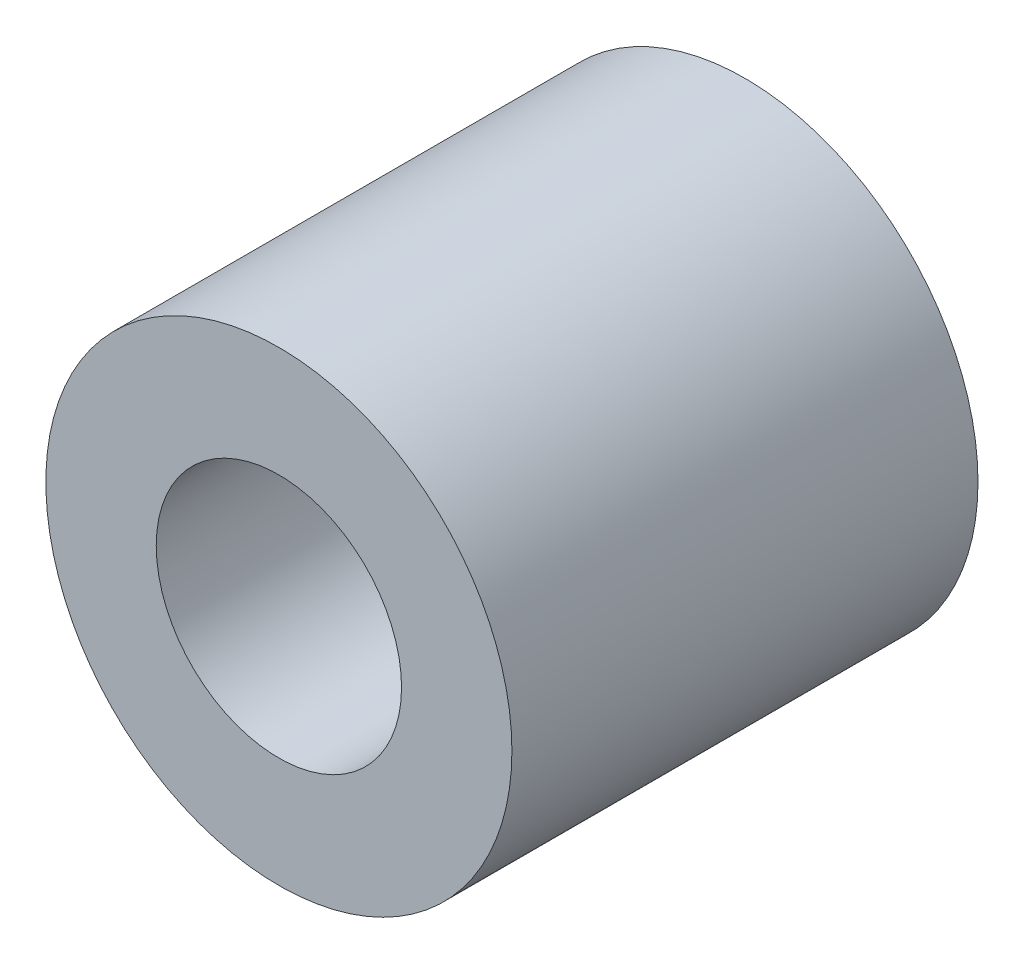
SolidWorks part; units mm, degrees
material "Nylon"
ref_plane "Front Plane" through (0, 0, 0) normal (0, 0, 1) x (1, 0, 0)
ref_plane "Top Plane" through (0, 0, 0) normal (0, 1, 0) x (1, 0, 0)
ref_plane "Right Plane" through (0, 0, 0) normal (1, 0, 0) x (0, 0, -1)
sketch "Sketch1" plane through (0, 0, 0) normal (0, 0, 1) x (1, 0, 0)
  circle A0 centre (0, 0) radius 4.75
  dimension "D1" = 9.5
extrude "Extrude1" add sketch "Sketch1" against normal blind 9.5
sketch "Sketch2" plane through (0, 0, 0) normal (0, 0, 1) x (1, 0, 0)
  circle A0 centre (0, 0) radius 2.5
  dimension "D1" = 5
extrude "Cut-Extrude1" cut sketch "Sketch2" against normal through all
